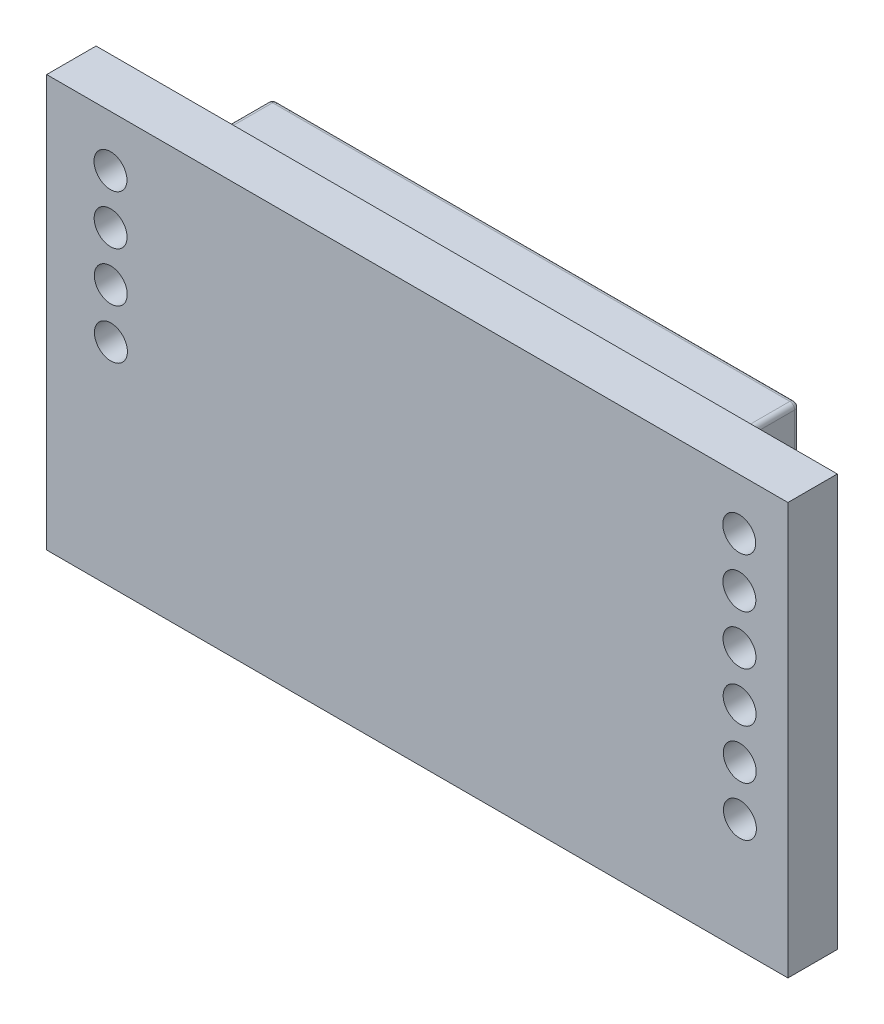
SolidWorks part; units mm, degrees
ref_plane "Front Plane" through (0, 0, 0) normal (0, 0, 1) x (1, 0, 0)
ref_plane "Top Plane" through (0, 0, 0) normal (0, 1, 0) x (1, 0, 0)
ref_plane "Right Plane" through (0, 0, 0) normal (1, 0, 0) x (0, 0, -1)
sketch "Sketch1" plane through (0, 0, 0) normal (0, 0, 1) x (1, 0, 0)
  line L1 (0, 0) -> (-45, 0)
  line L2 (0, 0) -> (0, 25)
  line L3 (0, 25) -> (-45, 25)
  line L4 (-45, 0) -> (-45, 25)
  dimension "D1" = 25
  dimension "D2" = 45
extrude "Boss-Extrude1" add sketch "Sketch1" along normal blind 3
sketch "Sketch2" plane through (0, 0, 0) normal (0, 0, 1) x (1, 0, 0)
  line L1 (-5.7881, 24.1709) -> (-37.7881, 24.1709)
  line L2 (-5.7881, 24.1709) -> (-5.7881, 2.1709)
  line L3 (-5.7881, 2.1709) -> (-37.7881, 2.1709)
  line L4 (-37.7881, 24.1709) -> (-37.7881, 2.1709)
  dimension "D1" = 32
  dimension "D2" = 22
extrude "Boss-Extrude2" add sketch "Sketch2" against normal blind 3.5 contours L2 L1 L4 L3
fillet "Fillet2" radius 0.3 1 edges at (-5.7881, 2.1709, -1.75)
fillet "Fillet3" radius 0.3 3 edges at (-5.7881, 13.3209, -3.5) (-5.876, 2.2587, -3.5) (-21.9381, 2.1709, -3.5)
fillet "Fillet4" radius 0.3 3 edges at (-37.7881, 2.1709, -1.6) (-37.7881, 2.2587, -3.4121) (-37.7881, 13.3209, -3.5)
fillet "Fillet5" radius 0.3 5 edges at (-5.7881, 24.1709, -1.6) (-5.876, 24.1709, -3.4121) (-37.7881, 24.1709, -1.6) (-37.7002, 24.1709, -3.4121) (-21.7881, 24.1709, -3.5)
sketch "Sketch3" plane through (0, 0, 0) normal (0, 0, -1) x (-1, 0, 0)
  line L0 (41.1263, 21.8864) -> (40.1263, 21.8864)
  line L1 (3.9554, 21.8864) -> (2.9554, 21.8864)
  line L2 (2.9554, 21.8864) -> (13.528, 21.8864)
  line L3 (13.528, 21.8864) -> (15.4807, 21.8864)
  circle A0 centre (41.1263, 21.8864) radius 1
  circle A1 centre (2.9554, 21.8864) radius 1
  circle A6 centre (41.1176, 18.8864) radius 1
  circle A7 centre (41.1089, 15.8864) radius 1
  circle A8 centre (41.1002, 12.8865) radius 1
  circle A9 centre (2.9474, 18.8864) radius 1
  circle A10 centre (2.9393, 15.8864) radius 1
  circle A11 centre (2.9313, 12.8865) radius 1
  circle A12 centre (2.9233, 9.8865) radius 1
  circle A13 centre (2.9153, 6.8865) radius 1
  dimension "D1" = 2
  dimension "D2" = 2
  dimension "D4" = 6
  dimension "D3" = 4
extrude "Cut-Extrude4" cut sketch "Sketch3" against normal blind 7.5 and the other way through all contours A9 | A10 | A1 | A11 | A12 | A13 | A8 | A7 | A6 | A0
sketch "Sketch4" plane through (0, 0, -3.5) normal (0, 0, -1) x (-1, 0, 0)
  text T0 "<b>KELOMPOK 16</b>" font "Century Gothic" height in points 5
